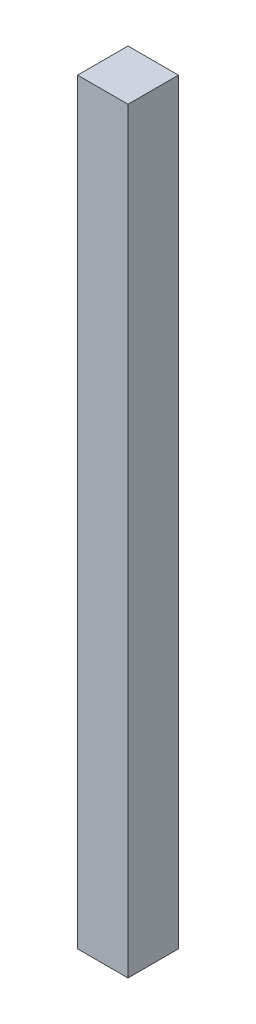
SolidWorks part; units mm, degrees
ref_plane "Front Plane" through (0, 0, 0) normal (0, 0, 1) x (1, 0, 0)
ref_plane "Top Plane" through (0, 0, 0) normal (0, 1, 0) x (1, 0, 0)
ref_plane "Right Plane" through (0, 0, 0) normal (1, 0, 0) x (0, 0, -1)
sketch "Sketch1" plane through (0, 0, 0) normal (0, 1, 0) x (1, 0, 0)
  line L1 (-0.5, -0.5) -> (0.5, -0.5)
  line L2 (-0.5, -0.5) -> (-0.5, 0.5)
  line L3 (-0.5, 0.5) -> (0.5, 0.5)
  line L4 (0.5, -0.5) -> (0.5, 0.5)
  line L5 (-0.5, -0.5) -> (0.5, 0.5) construction
  line L6 (-0.5, 0.5) -> (0.5, -0.5) construction
  point P0 (0, 0)
  dimension "D1" = 1
  dimension "D2" = 1
extrude "Boss-Extrude1" add sketch "Sketch1" along normal blind 15
